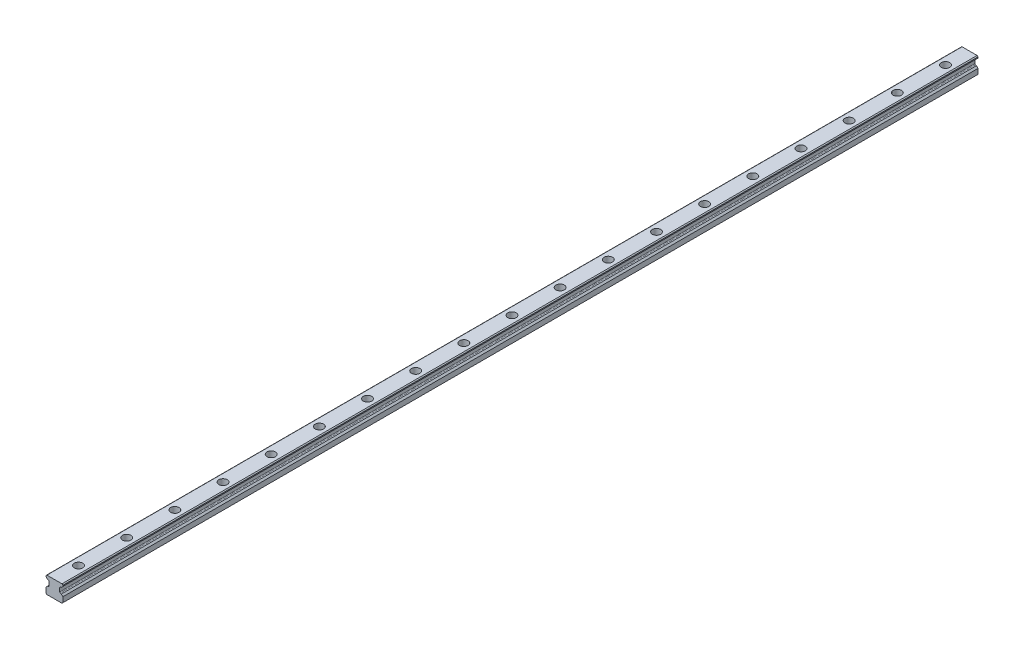
SolidWorks part; units mm, degrees
material "Alloy Steel"
ref_plane "Front" through (0, 0, 0) normal (0, 0, 1) x (1, 0, 0)
ref_plane "Top" through (0, 0, 0) normal (0, 1, 0) x (1, 0, 0)
ref_plane "Right" through (0, 0, 0) normal (1, 0, 0) x (0, 0, -1)
sketch "Sketch1" plane through (0, 0, 0) normal (0, 0, 1) x (1, 0, 0)
  line L36 (-9.9118, 13.1068) -> (-11.43, 12.7)
  line L37 (-11.43, 12.7) -> (-14, 10.13)
  line L38 (-14, 10.13) -> (-14, 1.5)
  line L39 (-14, 1.5) -> (-12.5, 0)
  line L40 (-12.5, 0) -> (12.5, 0)
  line L41 (12.5, 0) -> (14, 1.5)
  line L42 (14, 1.5) -> (14, 10.13)
  line L43 (14, 10.13) -> (11.43, 12.7)
  line L44 (11.43, 12.7) -> (9.9118, 13.1068)
  line L45 (8.8, 14.5557) -> (8.8, 20.4443)
  line L46 (9.9118, 21.8932) -> (11.43, 22.3)
  line L47 (11.43, 22.3) -> (14, 24.87)
  line L48 (14, 24.87) -> (14, 26.5)
  line L49 (12.5, 28) -> (-12.5, 28)
  line L50 (-14, 26.5) -> (-14, 24.87)
  line L51 (-14, 24.87) -> (-11.43, 22.3)
  line L52 (-11.43, 22.3) -> (-9.9118, 21.8932)
  line L53 (-8.8, 20.4443) -> (-8.8, 14.5557)
  arc A12 (8.8, 14.5557) -> (9.9118, 13.1068) centre (10.3, 14.5557) ccw
  arc A13 (9.9118, 21.8932) -> (8.8, 20.4443) centre (10.3, 20.4443) ccw
  arc A14 (14, 26.5) -> (12.5, 28) centre (11.6492, 25.6492) ccw
  arc A15 (-12.5, 28) -> (-14, 26.5) centre (-11.6492, 25.6492) ccw
  arc A16 (-8.8, 20.4443) -> (-9.9118, 21.8932) centre (-10.3, 20.4443) ccw
  arc A17 (-9.9118, 13.1068) -> (-8.8, 14.5557) centre (-10.3, 14.5557) ccw
extrude "Boss-Extrude1" add sketch "Sketch1" along normal mid plane 1520
sketch "Sketch2" plane through (0, 0, 0) normal (1, 0, 0) x (0, 0, -1)
  line L0 (-720, 28) -> (-720, 0) construction
  line L3 (-720, 28) -> (-713, 28)
  line L4 (-713, 28) -> (-713, 16)
  line L5 (-713, 16) -> (-715.5, 16)
  line L6 (-715.5, 16) -> (-715.5, 0)
  line L7 (-715.5, 0) -> (-720, 0)
  line L8 (-720, 0) -> (-720, 28)
  line L9 (-760, 28) -> (760, 28) construction
  line L10 (-760, 28) -> (-760, 26.5) construction
  line L11 (-760, 0) -> (760, 0) construction
  dimension "D1" = 40
  dimension "D2" = 14
  dimension "D3" = 9
  dimension "D4" = 12
revolve "Cut-Revolve1" cut sketch "Sketch2" angle 360 about L0
pattern_linear "LPattern1" count 2 spacing 80 along (0, 0, -1) of "Cut-Revolve1"
mirror "Mirror1" about plane through (0, 0, 0) normal (0, 0, 1) of "LPattern1", "Cut-Revolve1"
pattern_linear "LPattern2" count 9 spacing 160 along (0, 0, -1) of "LPattern1", "Cut-Revolve1"
sketch "Sketch3" plane through (0, 0, 0) normal (1, 0, 0) x (0, 0, -1)
  line L0 (-713, 28) -> (-713, 16) construction
  line L1 (-713, 16) -> (-715.5, 16) construction
  line L2 (-715.5, 16) -> (-715.5, 0) construction
  line L3 (-720, 28) -> (-713, 28) construction
  line L4 (-715.5, 0) -> (-720, 0) construction
  line L5 (-713, 28) -> (-713, 16)
  line L6 (-713, 16) -> (-715.5, 16)
  line L7 (-715.5, 16) -> (-715.5, 0)
  line L8 (-727, 28) -> (-713, 28)
  line L9 (-715.5, 0) -> (-724.5, 0)
  line L10 (-720, 28) -> (-720, 0) construction
  line L11 (-724.5, 16) -> (-724.5, 0)
  line L12 (-727, 16) -> (-724.5, 16)
  line L13 (-727, 28) -> (-727, 16)
  line L14 (-633, 28) -> (-633, 16)
  line L15 (-633, 16) -> (-635.5, 16)
  line L16 (-635.5, 16) -> (-635.5, 0)
  line L17 (-647, 28) -> (-633, 28)
  line L18 (-635.5, 0) -> (-644.5, 0)
  line L19 (-640, 28) -> (-640, 0) construction
  line L20 (-644.5, 16) -> (-644.5, 0)
  line L21 (-647, 16) -> (-644.5, 16)
  line L22 (-647, 28) -> (-647, 16)
  line L23 (-644.5, 0) -> (-635.5, 0) construction
  line L24 (727, 28) -> (727, 16)
  line L25 (727, 16) -> (724.5, 16)
  line L26 (724.5, 16) -> (724.5, 0)
  line L27 (713, 28) -> (727, 28)
  line L28 (724.5, 0) -> (715.5, 0)
  line L29 (720, 28) -> (720, 0) construction
  line L30 (715.5, 16) -> (715.5, 0)
  line L31 (713, 16) -> (715.5, 16)
  line L32 (713, 28) -> (713, 16)
  line L33 (715.5, 0) -> (724.5, 0) construction
ref_plane "Plane1" through (0, 0, 720) normal (0, 0, 1) x (1, 0, 0)
sketch "Sketch4" plane through (0, 0, 720) normal (0, 0, 1) x (1, 0, 0)
  line L0 (-7, 28) -> (7, 28)
  line L1 (7, 28) -> (-7, 28) construction
  line L2 (12.5, 28) -> (-12.5, 28) construction
  line L3 (7, 28) -> (7, 16)
  line L4 (7, 16) -> (-7, 16) construction
  line L5 (7, 16) -> (4.5, 16)
  line L6 (4.5, 16) -> (-4.5, 16) construction
  line L7 (4.5, 16) -> (4.5, 0)
  line L8 (4.5, 0) -> (-4.5, 0)
  line L9 (-4.5, 0) -> (4.5, 0) construction
  line L10 (0, 0) -> (0, 28) construction
  line L11 (-4.5, 16) -> (-4.5, 0)
  line L12 (-7, 16) -> (-4.5, 16)
  line L13 (-7, 28) -> (-7, 16)
equation "\"D3@LPattern2\"=\"D3@LPattern1\"*2"
